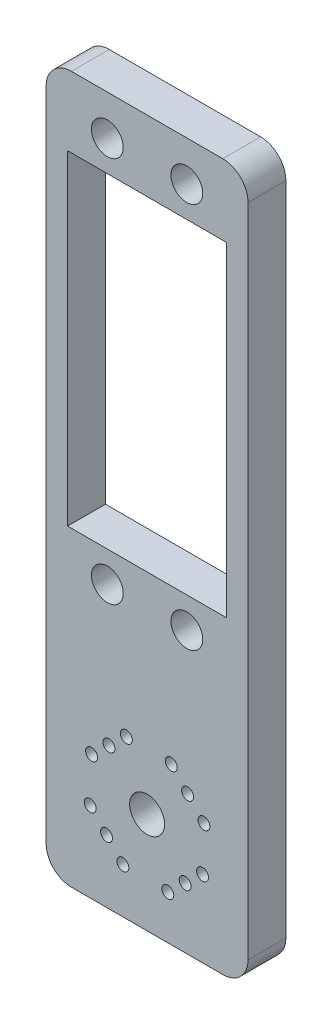
SolidWorks part; units mm, degrees
ref_plane "Front Plane" through (0, 0, 0) normal (0, 0, 1) x (1, 0, 0)
ref_plane "Top Plane" through (0, 0, 0) normal (0, 1, 0) x (1, 0, 0)
ref_plane "Right Plane" through (0, 0, 0) normal (1, 0, 0) x (0, 0, -1)
sketch "Sketch1" plane through (0, 0, 0) normal (0, 0, 1) x (1, 0, 0)
  line L1 (0, 0) -> (25.4, 0)
  line L2 (0, 0) -> (0, 88.9)
  line L3 (0, 88.9) -> (25.4, 88.9)
  line L4 (25.4, 0) -> (25.4, 88.9)
  point P5 (12.7, 0)
  point P8 (12.7, 39.11)
  circle B0 centre (12.7, 12.7) radius 1.5
  circle B1 centre (10.0921, 19.8554) radius 0.75
  circle B2 centre (7.9061, 17.8008) radius 0.75
  circle B3 centre (5.72, 15.7463) radius 0.75
  circle B4 centre (5.5446, 10.0921) radius 0.75
  circle B5 centre (7.5992, 7.9061) radius 0.75
  circle B6 centre (9.6537, 5.72) radius 0.75
  circle B7 centre (15.3079, 5.5446) radius 0.75
  circle B8 centre (17.4939, 7.5992) radius 0.75
  circle B9 centre (19.68, 9.6537) radius 0.75
  circle B10 centre (19.8554, 15.3079) radius 0.75
  circle B11 centre (17.8008, 17.4939) radius 0.75
  circle B12 centre (15.7463, 19.68) radius 0.75
  circle B13 centre (12.7, 12.7) radius 10
  line B14 (7.7, 83.86) -> (7.7, 35.26) construction
  line B15 (7.7, 83.86) -> (17.7, 83.86) construction
  line B16 (2.7, 39.11) -> (22.7, 39.11)
  line B17 (2.7, 39.11) -> (2.7, 80.01)
  line B18 (2.7, 80.01) -> (22.7, 80.01)
  line B19 (22.7, 39.11) -> (22.7, 80.01)
  circle B20 centre (7.7, 83.86) radius 2
  circle B21 centre (17.7, 83.86) radius 2
  circle B22 centre (7.7, 35.26) radius 2
  circle B23 centre (17.7, 35.26) radius 2
  dimension "D1" = 25.4
  dimension "D2" = 88.9
  dimension "D3" = 12.7
  dimension "D4" = 8.89
sketch_block_instance "ServoHornBlock-1"
sketch_block "ServoHornBlock"
sketch_block_instance "ServoBlock-1"
sketch_block "ServoBlock" parameters "D1"=4, "D2"=10, "D3"=48.6, "D4"=40.9, "D5"=20
extrude "Boss-Extrude1" add sketch "Sketch1" along normal blind 4.7625 contours L1 L4 L3 L2 B23 B22 B21 B20 B19 B16 B17 B18 B13 | B13 B0 B1 B2 B3 B4 B5 B6 B7 B8 B9 B10 B11 B12
fillet "Fillet1" radius 3.175 4 edges at (0, 88.9, 2.3813) (25.4, 88.9, 2.3813) (25.4, 0, 2.3813) (0, 0, 2.3813)
sketch "Sketch2" plane through (0, 0, 4.7625) normal (0, 0, 1) x (1, 0, 0)
  circle A0 centre (12.7, 12.7) radius 2.2
  dimension "D1" = 4.4
extrude "Cut-Extrude1" cut sketch "Sketch2" against normal through all
